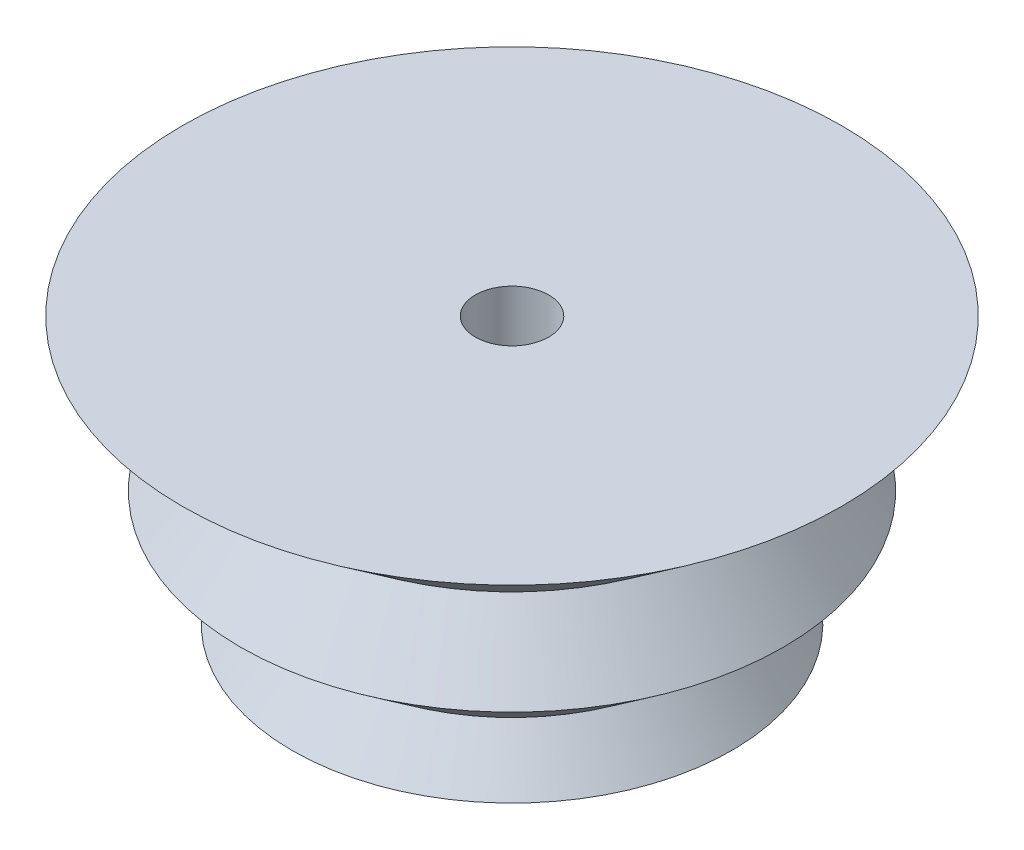
SolidWorks part; units mm, degrees
ref_plane "Front Plane" through (0, 0, 0) normal (0, 0, 1) x (1, 0, 0)
ref_plane "Top Plane" through (0, 0, 0) normal (0, 1, 0) x (1, 0, 0)
ref_plane "Right Plane" through (0, 0, 0) normal (1, 0, 0) x (0, 0, -1)
sketch "Sketch1" plane through (0, 0, 0) normal (0, 0, 1) x (1, 0, 0)
  line L0 (0, 0) -> (3, 0)
  line L1 (3, 0) -> (2.5, 0.6575)
  line L2 (2.5, 0.6575) -> (3.7026, 1.572)
  line L3 (3.7026, 1.572) -> (3, 2.496)
  line L4 (3, 2.496) -> (4.5, 3.6366)
  line L5 (4.5, 3.6366) -> (0, 3.6366)
  line L6 (0, 3.6366) -> (0, 0)
  dimension "D1" = 3
  dimension "D2" = 4.5
  dimension "D3" = 3
  dimension "D4" = 2.5
revolve "Revolve1" add sketch "Sketch1" angle 360 about L6
sketch "Sketch2" plane through (0, 3.6366, 0) normal (0, 1, 0) x (1, 0, 0)
  circle A0 centre (0, 0) radius 0.5
extrude "Cut-Extrude1" cut sketch "Sketch2" against normal through all
